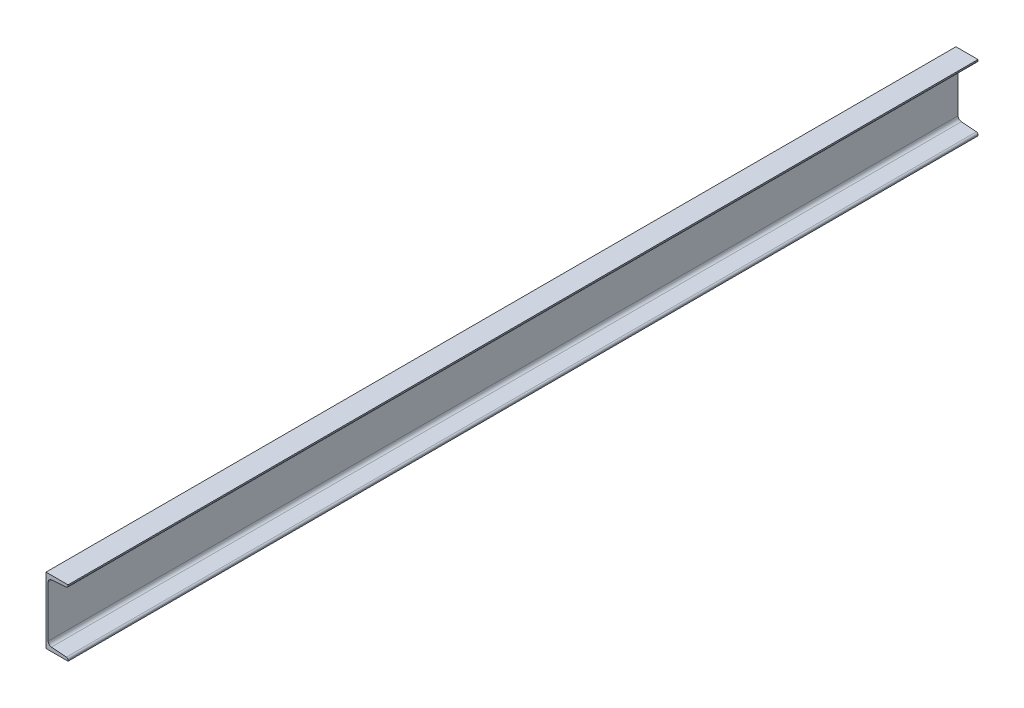
SolidWorks part; units mm, degrees
ref_plane "Front Plane" through (0, 0, 0) normal (0, 0, 1) x (1, 0, 0)
ref_plane "Top Plane" through (0, 0, 0) normal (0, 1, 0) x (1, 0, 0)
ref_plane "Right Plane" through (0, 0, 0) normal (1, 0, 0) x (0, 0, -1)
sketch "Model" plane through (0, 0, 0) normal (0, 0, 1) x (1, 0, 0)
  line L0 (5066.5854, 3271.4798) -> (5066.5854, 3266.914)
  line L1 (5066.5854, 3271.4798) -> (4966.5854, 3271.4798)
  line L2 (4966.5854, 3271.4798) -> (4966.5854, 2971.4798)
  line L3 (4976.5854, 3237.4798) -> (4976.5854, 3005.4798)
  line L4 (5016.5854, 3271.4798) -> (5016.5854, 3255.4798) construction
  line L5 (4991.2914, 2989.5322) -> (5059.2325, 2984.0193)
  line L6 (5066.5854, 2971.4798) -> (4966.5854, 2971.4798)
  line L7 (5066.5854, 2971.4798) -> (5066.5854, 2976.0455)
  line L8 (5059.2325, 3258.9402) -> (5059.2325, 3271.4798) construction
  line L9 (4966.5854, 3121.4798) -> (4986.6759, 3121.4798) construction
  line L10 (4991.2914, 3253.4274) -> (5059.2325, 3258.9402)
  arc A0 (5066.5854, 2976.0455) -> (5059.2325, 2984.0193) centre (5058.5854, 2976.0455) ccw
  arc A1 (4991.2914, 2989.5322) -> (4976.5854, 3005.4798) centre (4992.5854, 3005.4798) cw
  arc A2 (4991.2914, 3253.4274) -> (4976.5854, 3237.4798) centre (4992.5854, 3237.4798) ccw
  arc A3 (5066.5854, 3266.914) -> (5059.2325, 3258.9402) centre (5058.5854, 3266.914) cw
  point P15 (4976.5854, 3121.4798)
  point P22 (4976.5854, 3121.4798)
  dimension "r1" = 16
  dimension "r2" = 8
  dimension "bf" = 100
  dimension "tw" = 10
  dimension "tf" = 16
  dimension "H/2" = 150
  dimension "hw" = 116
extrude "Boss-Extrude1" add sketch "Model" along normal blind 4125
